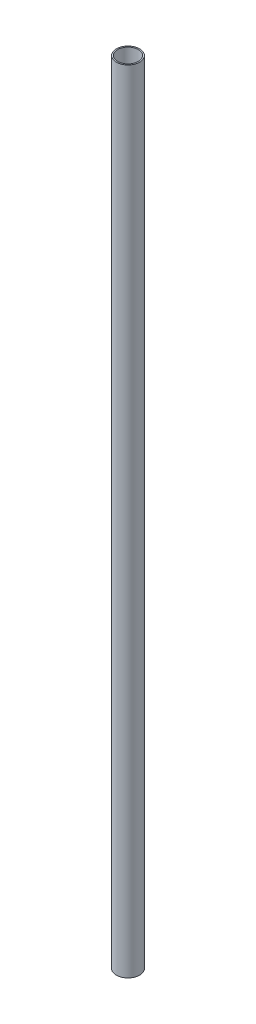
SolidWorks part; units mm, degrees
material "6061-T6 (SS)"
ref_plane "Front Plane" through (0, 0, 0) normal (0, 0, 1) x (1, 0, 0)
ref_plane "Top Plane" through (0, 0, 0) normal (0, 1, 0) x (1, 0, 0)
ref_plane "Right Plane" through (0, 0, 0) normal (1, 0, 0) x (0, 0, -1)
sketch "Sketch2" plane through (0, 0, 0) normal (0, 1, 0) x (1, 0, 0)
  circle A0 centre (0, 0) radius 7.9375
  circle A1 centre (0, 0) radius 7.0485
  dimension "D1" = 15.875
  dimension "D2" = 0.889
extrude "Boss-Extrude1" add sketch "Sketch2" along normal blind 539.75
